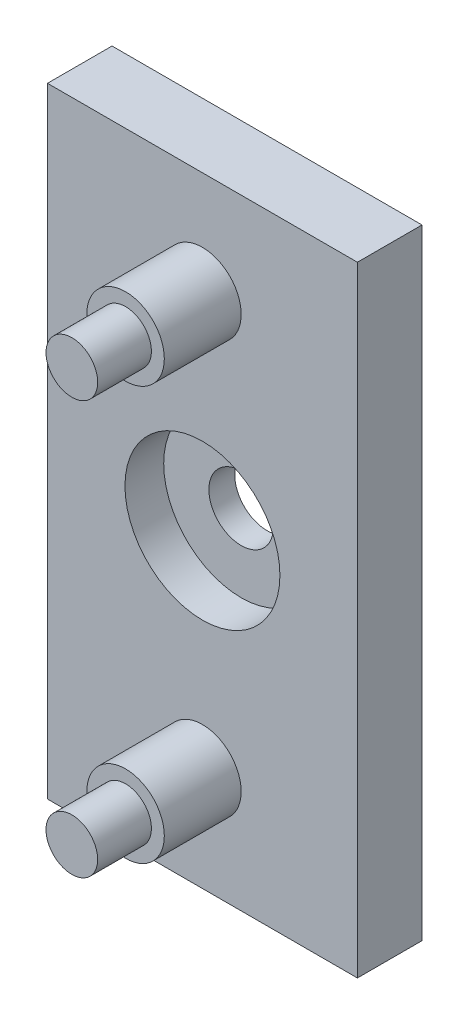
SolidWorks part; units mm, degrees
ref_plane "Front Plane" through (0, 0, 0) normal (0, 0, 1) x (1, 0, 0)
ref_plane "Top Plane" through (0, 0, 0) normal (0, 1, 0) x (1, 0, 0)
ref_plane "Right Plane" through (0, 0, 0) normal (1, 0, 0) x (0, 0, -1)
sketch "Sketch1" plane through (0, 0, 0) normal (0, 0, 1) x (1, 0, 0)
  line L1 (-19.05, -38.1) -> (19.05, -38.1)
  line L2 (-19.05, -38.1) -> (-19.05, 38.1)
  line L3 (-19.05, 38.1) -> (19.05, 38.1)
  line L4 (19.05, -38.1) -> (19.05, 38.1)
  line L5 (-19.05, -38.1) -> (19.05, 38.1) construction
  line L6 (-19.05, 38.1) -> (19.05, -38.1) construction
  point P0 (0, 0)
  dimension "D1" = 38.1
  dimension "D2" = 76.2
extrude "Boss-Extrude1" add sketch "Sketch1" along normal blind 7.9375
sketch "Sketch2" plane through (0, 0, 7.9375) normal (0, 0, 1) x (1, 0, 0)
  circle A0 centre (0, 0) radius 3.9688
  dimension "D1" = 7.9375
extrude "Cut-Extrude1" cut sketch "Sketch2" against normal through all
sketch "Sketch4" plane through (0, 0, 7.9375) normal (0, 0, 1) x (1, 0, 0)
  circle A0 centre (0, 0) radius 9.525
  dimension "D1" = 19.05
extrude "Cut-Extrude2" cut sketch "Sketch4" against normal offset from surface (4.7625 mm away) 3.175 up to face at (3.9688, 0, 0)
sketch "Sketch5" plane through (0, 0, 7.9375) normal (0, 0, 1) x (1, 0, 0)
  line L0 (19.05, 38.1) -> (-19.05, 38.1) construction
  circle A0 centre (0, 25.4) radius 4.7625
  point P2 (0, 0)
  dimension "D1" = 9.525
  dimension "D2" = 12.7
extrude "Boss-Extrude2" add sketch "Sketch5" along normal blind 9.4488
sketch "Sketch6" plane through (0, 0, 17.3863) normal (0, 0, 1) x (1, 0, 0)
  circle A0 centre (0, 25.4) radius 3.175
  dimension "D1" = 6.35
extrude "Boss-Extrude3" add sketch "Sketch6" along normal blind 6.604
mirror "Mirror1" about plane through (0, 0, 0) normal (0, 1, 0) of "Boss-Extrude2", "Boss-Extrude3"
